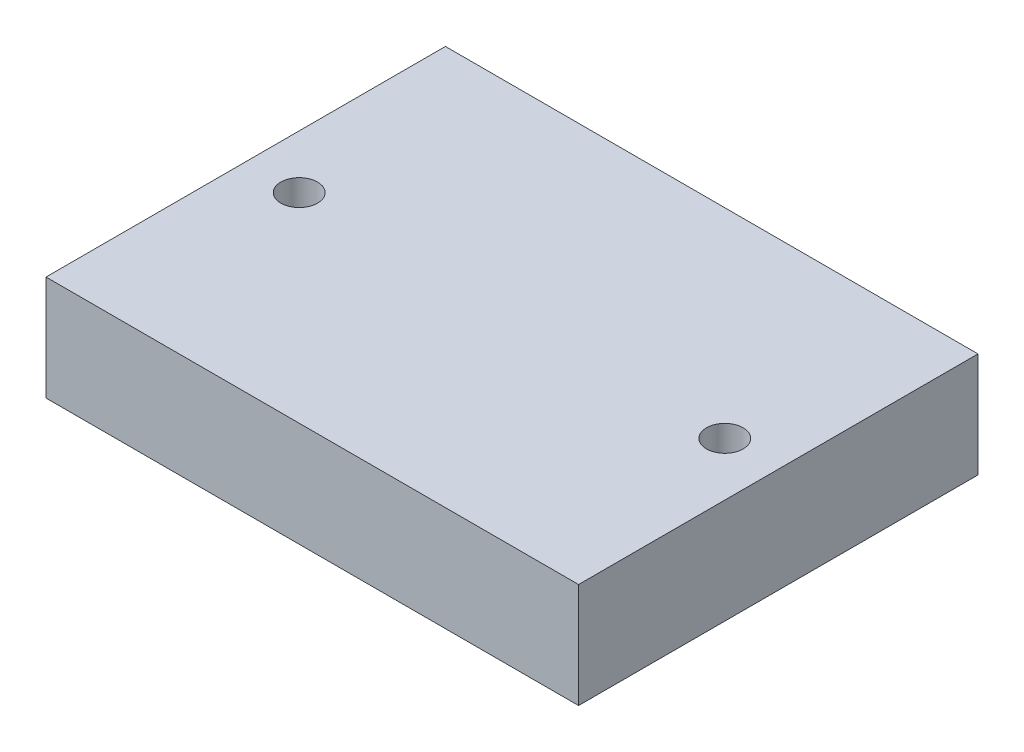
SolidWorks part; units mm, degrees
ref_plane "Front Plane" through (0, 0, 0) normal (0, 0, 1) x (1, 0, 0)
ref_plane "Top Plane" through (0, 0, 0) normal (0, 1, 0) x (1, 0, 0)
ref_plane "Right Plane" through (0, 0, 0) normal (1, 0, 0) x (0, 0, -1)
sketch "Sketch1" plane through (0, 0, 0) normal (0, 1, 0) x (1, 0, 0)
  line L1 (0, 0) -> (50.8, 0)
  line L2 (0, 0) -> (0, 38.1)
  line L3 (0, 38.1) -> (50.8, 38.1)
  line L4 (50.8, 0) -> (50.8, 38.1)
  circle A0 centre (5.1, 19.05) radius 1.75
  circle A1 centre (45.7, 19.05) radius 1.75
  point P9 (0, 0)
  dimension "D4" = 5.1
  dimension "D5" = 3.5
  dimension "D1" = 38.1
  dimension "D2" = 50.8
  dimension "D3" = 5.1
extrude "Boss-Extrude1" add sketch "Sketch1" along normal blind 10
